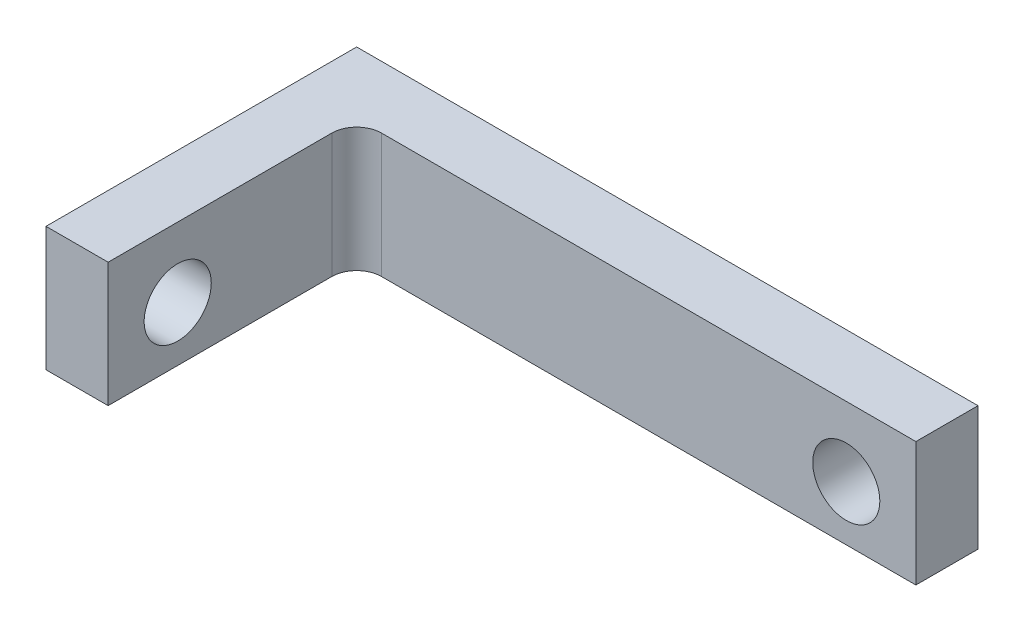
SolidWorks part; units mm, degrees
ref_plane "Front Plane" through (0, 0, 0) normal (0, 0, 1) x (1, 0, 0)
ref_plane "Top Plane" through (0, 0, 0) normal (0, 1, 0) x (1, 0, 0)
ref_plane "Right Plane" through (0, 0, 0) normal (1, 0, 0) x (0, 0, -1)
sketch "Sketch1" plane through (0, 0, 0) normal (0, 1, 0) x (1, 0, 0)
  line L0 (-25, 0) -> (25, 0)
  line L1 (-25, 0) -> (-25, -25)
  line L2 (-25, -25) -> (-20, -25)
  line L3 (25, 0) -> (25, -5)
  line L10 (-20, -25) -> (-20, -5)
  line L11 (-20, -5) -> (25, -5)
  dimension "D1" = 50
  dimension "D2" = 25
  dimension "D3" = 5
  dimension "D4" = 5
extrude "Boss-Extrude1" add sketch "Sketch1" along normal blind 10
sketch "Sketch2" plane through (-20, 0, 0) normal (1, 0, 0) x (0, 0, -1)
  line L0 (-25, 10) -> (-25, 0) construction
  line L3 (-25, 10) -> (-5, 10) construction
  circle A0 centre (-19.4, 4.4) radius 2.7
  dimension "D1" = 5.4
  dimension "D2" = 5.6
  dimension "D3" = 5.6
extrude "Cut-Extrude1" cut sketch "Sketch2" against normal through all
sketch "Sketch3" plane through (0, 0, 5) normal (0, 0, 1) x (1, 0, 0)
  line L0 (25, 10) -> (25, 0) construction
  line L1 (-20, 10) -> (25, 10) construction
  circle A0 centre (19.4, 4.4) radius 2.7
  dimension "D1" = 5.4
  dimension "D2" = 5.6
  dimension "D3" = 5.6
extrude "Cut-Extrude2" cut sketch "Sketch3" against normal through all
fillet "Fillet1" radius 2 1 edges at (-20, 5, 5)
